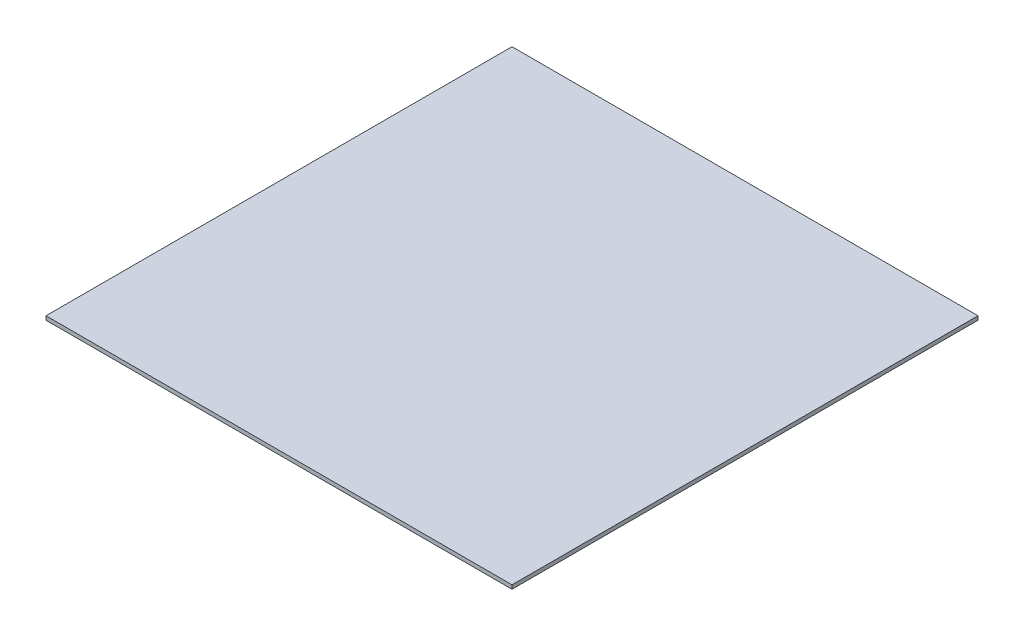
SolidWorks part; units mm, degrees
ref_plane "Alzado" through (0, 0, 0) normal (0, 0, 1) x (1, 0, 0)
ref_plane "Planta" through (0, 0, 0) normal (0, 1, 0) x (1, 0, 0)
ref_plane "Vista lateral" through (0, 0, 0) normal (1, 0, 0) x (0, 0, -1)
sketch "Croquis1" plane through (0, 0, 0) normal (0, 1, 0) x (1, 0, 0)
  line L1 (-60, 60) -> (60, 60)
  line L2 (-60, 60) -> (-60, -60)
  line L3 (-60, -60) -> (60, -60)
  line L4 (60, 60) -> (60, -60)
  line L5 (-60, 60) -> (60, -60) construction
  line L6 (-60, -60) -> (60, 60) construction
  point P0 (0, 0)
  dimension "D1" = 120
  dimension "D2" = 120
extrude "Saliente-Extruir1" add sketch "Croquis1" along normal blind 1
